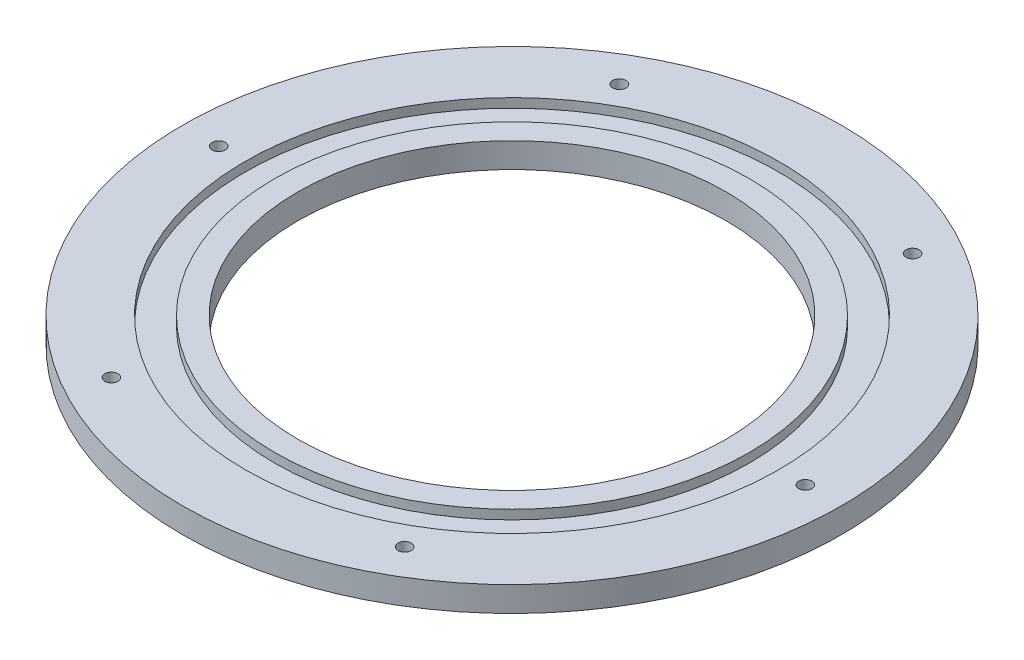
SolidWorks part; units mm, degrees
material "Pine"
ref_plane "Front Plane" through (0, 0, 0) normal (0, 0, 1) x (1, 0, 0)
ref_plane "Top Plane" through (0, 0, 0) normal (0, 1, 0) x (1, 0, 0)
ref_plane "Right Plane" through (0, 0, 0) normal (1, 0, 0) x (0, 0, -1)
sketch "Sketch1" plane through (0, 0, 0) normal (0, 1, 0) x (1, 0, 0)
  circle A0 centre (0, 0) radius 250
  circle A1 centre (0, 0) radius 162.5
  dimension "D1" = 500
  dimension "D2" = 325
extrude "Boss-Extrude1" add sketch "Sketch1" along normal mid plane 19
sketch "Sketch2" plane through (0, 9.5, 0) normal (0, 1, 0) x (1, 0, 0)
  circle A0 centre (0, 0) radius 180
  circle A1 centre (0, 0) radius 202.5
  dimension "D1" = 360
  dimension "D2" = 405
extrude "Cut-Extrude1" cut sketch "Sketch2" against normal blind 7
sketch "Sketch3" plane through (0, 9.5, 0) normal (0, 1, 0) x (1, 0, 0)
  line L0 (-1000, 0) -> (49000, 0) construction
  line L1 (0, -1000) -> (0, 49000) construction
  line L2 (-500, -866.0254) -> (24500, 42435.2448) construction
  line L3 (-500, 866.0254) -> (24500, -42435.2448) construction
  circle A0 centre (111.25, 192.6907) radius 5
  circle A1 centre (222.5, 0) radius 5
  circle A2 centre (-222.5, 0) radius 5
  circle A3 centre (-111.25, 192.6907) radius 5
  circle A4 centre (111.25, -192.6907) radius 5
  circle A5 centre (-111.25, -192.6907) radius 5
  dimension "D1" = 10
  dimension "D2" = 10
  dimension "D4" = 222.5
  dimension "D3" = 222.5
extrude "Cut-Extrude2" cut sketch "Sketch3" against normal through all
